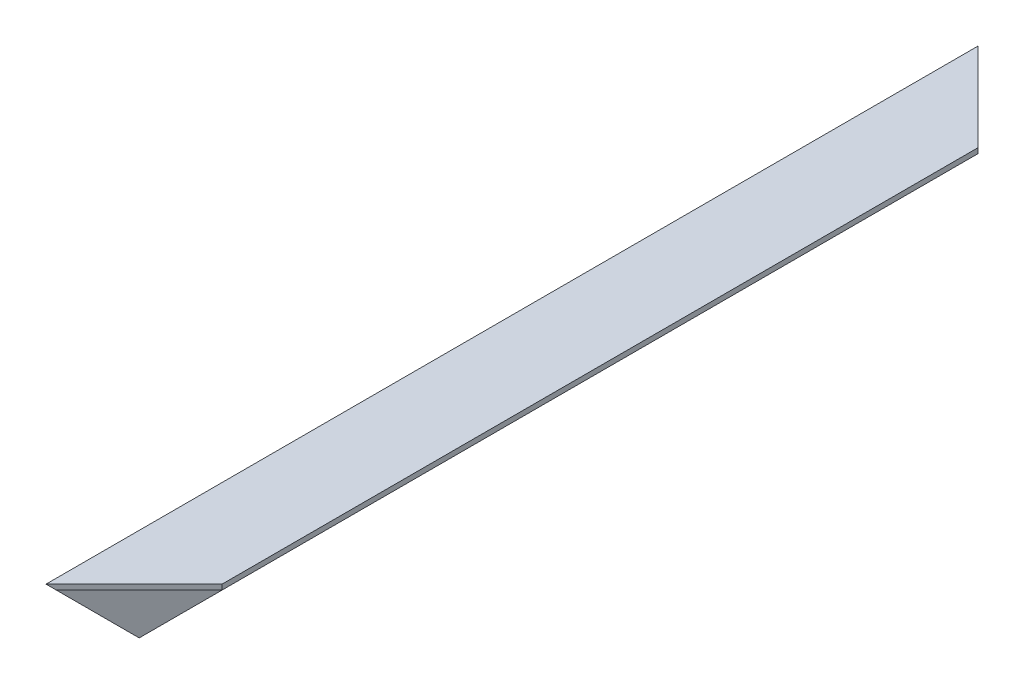
SolidWorks part; units mm, degrees
material "Ст 3 ГОСТ 380-88"
ref_plane "Front Plane" through (0, 0, 0) normal (0, 0, 1) x (1, 0, 0)
ref_plane "Top Plane" through (0, 0, 0) normal (0, 1, 0) x (1, 0, 0)
ref_plane "Right Plane" through (0, 0, 0) normal (1, 0, 0) x (0, 0, -1)
sketch "Sketch1" plane through (0, 0, 0) normal (0, 0, 1) x (1, 0, 0)
  line L0 (0, 42.7885) -> (0, -29.0064) construction
  line L1 (-43.5897, 0) -> (38.7821, 0) construction
  line L2 (-17.9063, 20.1835) -> (-17.9063, -22.3165)
  line L3 (-17.9063, -22.3165) -> (-15.4063, -22.3165)
  line L4 (-15.4063, -22.3165) -> (-15.4063, 17.6835)
  line L5 (-15.4063, 17.6835) -> (24.5937, 17.6835)
  line L6 (24.5937, 17.6835) -> (24.5937, 20.1835)
  line L7 (24.5937, 20.1835) -> (-17.9063, 20.1835)
  dimension "D1" = 40
  dimension "D2" = 40
  dimension "D3" = 2.5
extrude "Boss-Extrude1" add sketch "Sketch1" along normal mid plane 450
sketch "Sketch2" plane through (0, 20.1835, 0) normal (0, 1, 0) x (1, 0, 0)
  line L4 (-161.8368, 0) -> (169.307, 0) construction
  line L8 (24.5937, 182.5) -> (24.5937, 225)
  line L9 (24.5937, -225) -> (24.5937, 225) construction
  line L10 (24.5937, 225) -> (-17.9063, 225)
  line L11 (-17.9063, 225) -> (24.5937, 182.5)
  line L12 (24.5937, -225) -> (-17.9063, -225)
  line L13 (24.5937, -182.5) -> (24.5937, -225)
  line L14 (-17.9063, -225) -> (24.5937, -182.5)
  dimension "D1" = 42.5
extrude "Cut-Extrude2" cut sketch "Sketch2" against normal through all both and the other way through all
sketch "Sketch3" plane through (-17.9063, 0, 0) normal (-1, 0, 0) x (0, 0, 1)
  line L0 (-225, 20.1835) -> (-182.5, -22.3165)
  line L1 (225, -22.3165) -> (-225, -22.3165) construction
  line L2 (-182.5, -22.3165) -> (-225, -22.3165)
  line L3 (-225, -22.3165) -> (-225, 20.1835)
  line L4 (0, 118.9196) -> (0, -97.3418) construction
  line L5 (182.5, -22.3165) -> (225, -22.3165)
  line L6 (225, 20.1835) -> (182.5, -22.3165)
  line L7 (225, -22.3165) -> (225, 20.1835)
  dimension "D1" = 42.5
extrude "Cut-Extrude3" cut sketch "Sketch3" against normal through all both and the other way through all
